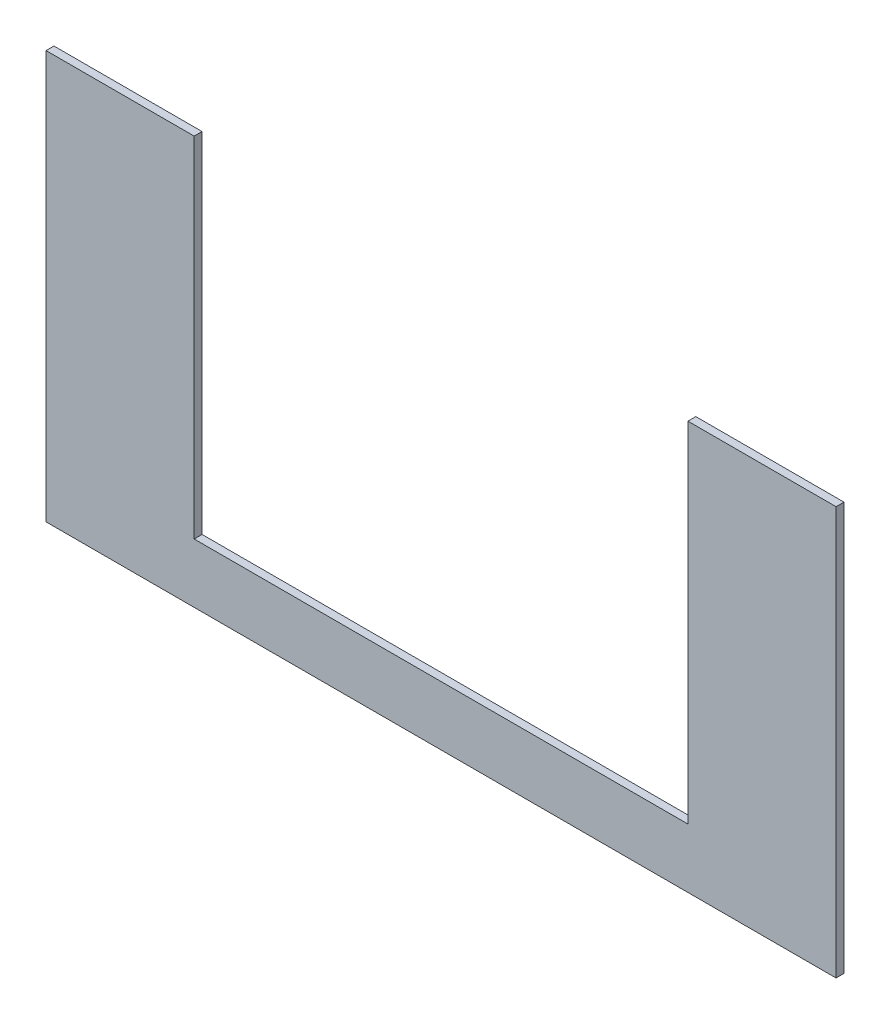
SolidWorks part; units mm, degrees
ref_plane "Front" through (0, 0, 0) normal (0, 0, 1) x (1, 0, 0)
ref_plane "Top" through (0, 0, 0) normal (0, 1, 0) x (1, 0, 0)
ref_plane "Right" through (0, 0, 0) normal (1, 0, 0) x (0, 0, -1)
sketch "Эскиз1" plane through (0, 0, 0) normal (0, 0, 1) x (1, 0, 0)
  line L0 (-592.6187, -146.0099) -> (-480.1187, -146.0099)
  line L1 (-1080.1187, -146.0099) -> (-967.6187, -146.0099)
  line L2 (-1080.1187, -146.0099) -> (-1080.1187, -456.0099)
  line L3 (-1080.1187, -456.0099) -> (-480.1187, -456.0099)
  line L4 (-480.1187, -146.0099) -> (-480.1187, -456.0099)
  line L6 (-967.6187, -146.0099) -> (-967.6187, -411.0099)
  line L7 (-967.6187, -411.0099) -> (-592.6187, -411.0099)
  line L8 (-592.6187, -146.0099) -> (-592.6187, -411.0099)
  line L9 (-780.1187, -456.0099) -> (-780.1187, 62.7649) construction
  point P10 (-780.1187, -411.0099)
  dimension "D1" = 375
  dimension "D2" = 600
  dimension "D3" = 310
  dimension "D4" = 265
extrude "Бобышка-Вытянуть1" add sketch "Эскиз1" along normal blind 6
